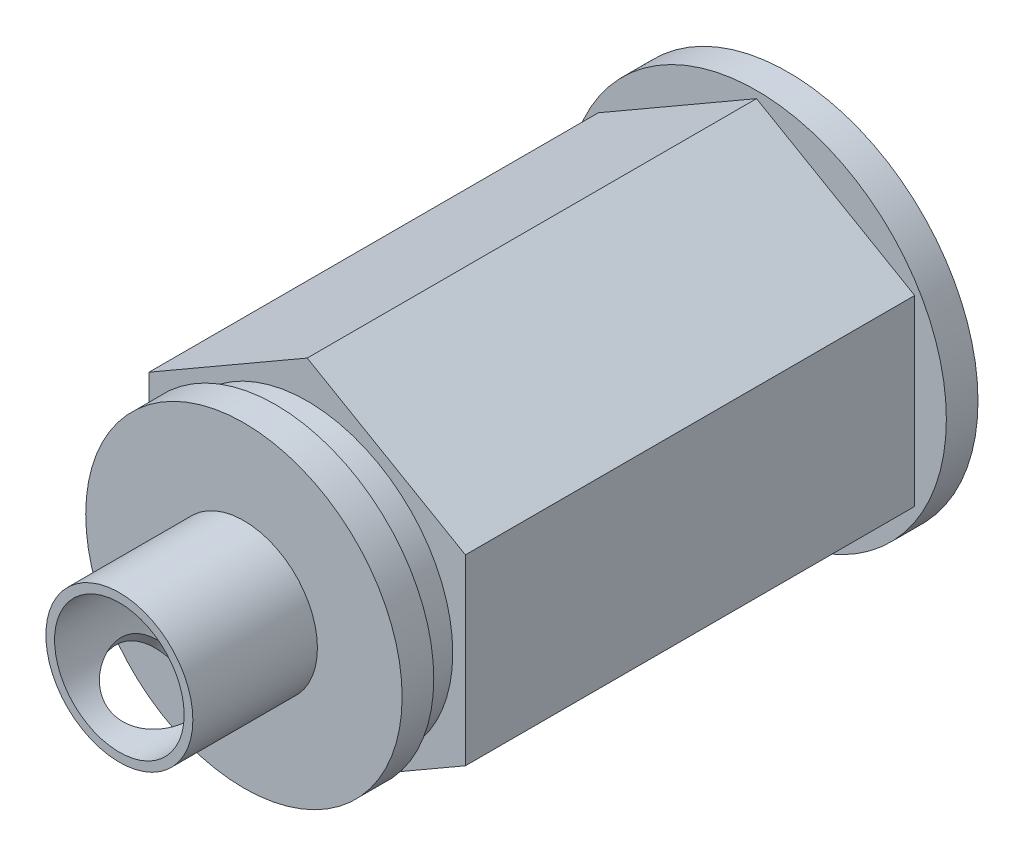
SolidWorks part; units mm, degrees
material "7075-O (SS)"
ref_plane "Plan de face" through (0, 0, 0) normal (0, 0, 1) x (1, 0, 0)
ref_plane "Plan de dessus" through (0, 0, 0) normal (0, 1, 0) x (1, 0, 0)
ref_plane "Plan de droite" through (0, 0, 0) normal (1, 0, 0) x (0, 0, -1)
sketch "Esquisse1" plane through (0, 0, 0) normal (0, 0, 1) x (1, 0, 0)
  line L1 (0, 7.3323) -> (-6.35, 3.6662)
  line L2 (-6.35, 3.6662) -> (-6.35, -3.6662)
  line L3 (-6.35, -3.6662) -> (0, -7.3323)
  line L4 (0, -7.3323) -> (6.35, -3.6662)
  line L5 (6.35, -3.6662) -> (6.35, 3.6662)
  line L6 (6.35, 3.6662) -> (0, 7.3323)
  circle A0 centre (0, 0) radius 6.35 construction
  dimension "D1" = 12.7
extrude "Boss.-Extru.1" add sketch "Esquisse1" along normal blind 19.304
sketch "Esquisse2" plane through (0, 0, 0) normal (0, 0, 1) x (1, 0, 0)
  circle A0 centre (0, 0) radius 7.62
  dimension "D1" = 15.24
extrude "Boss.-Extru.2" add sketch "Esquisse2" along normal blind 1.27
sketch "Esquisse3" plane through (0, 0, 19.304) normal (0, 0, 1) x (1, 0, 0)
  circle A0 centre (0, 0) radius 5.842
  dimension "D1" = 11.684
extrude "Boss.-Extru.3" add sketch "Esquisse3" along normal blind 1.27
sketch "Esquisse4" plane through (0, 0, 20.574) normal (0, 0, 1) x (1, 0, 0)
  circle A0 centre (0, 0) radius 6.35
  dimension "D1" = 12.7
extrude "Boss.-Extru.4" add sketch "Esquisse4" along normal blind 1.27
sketch "Esquisse5" plane through (0, 0, 0) normal (0, 0, 1) x (1, 0, 0)
  circle A0 centre (0, 0) radius 2.525
  dimension "D1" = 5.05
extrude "Enlèv. mat.-Extru.1" cut sketch "Esquisse5" along normal through all
sketch "Esquisse7" plane through (0, 0, 21.844) normal (0, 0, 1) x (1, 0, 0)
  circle A0 centre (0, 0) radius 2.6
  circle A1 centre (0, 0) radius 2.95
  dimension "D1" = 5.2
  dimension "D2" = 5.9
extrude "Boss.-Extru.6" add sketch "Esquisse7" along normal blind 5
sketch "Esquisse8" plane through (-3.175, -5.4993, 0) normal (-0.5, -0.866, 0) x (0.866, -0.5, 0)
  line L0 (6.35, 21.844) -> (-6.35, 21.844) construction
  line L2 (0, 24.384) -> (0, 21.844) construction
  circle A0 centre (0, 24.384) radius 1.55
  dimension "D1" = 3.1
  dimension "D2" = 2.54
extrude "Enlèv. mat.-Extru.2" cut sketch "Esquisse8" against normal blind 5
